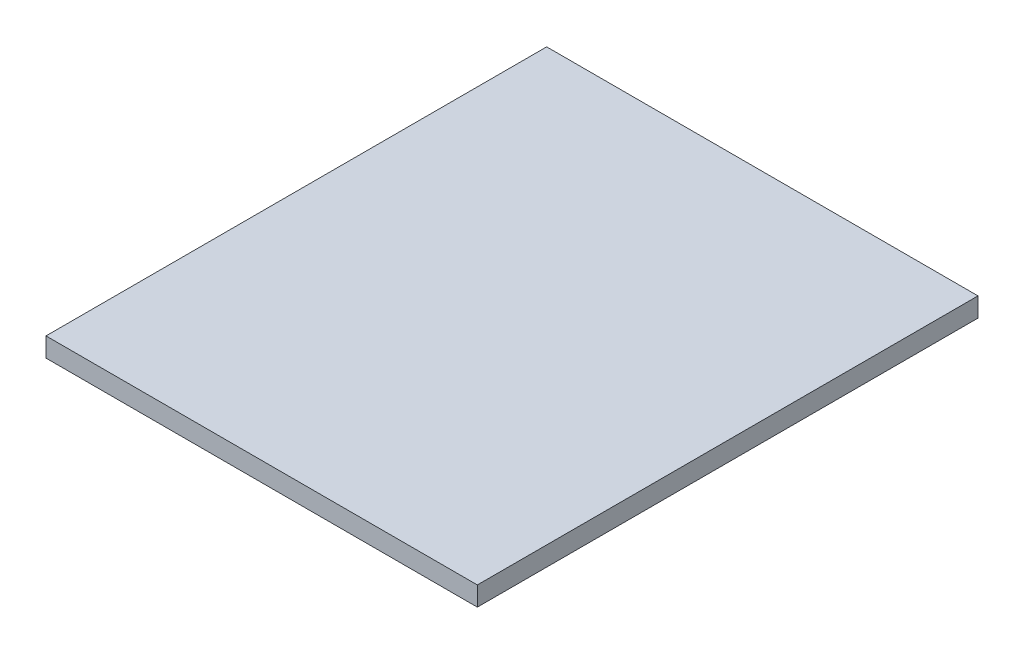
SolidWorks part; units mm, degrees
ref_plane "Front Plane" through (0, 0, 0) normal (0, 0, 1) x (1, 0, 0)
ref_plane "Top Plane" through (0, 0, 0) normal (0, 1, 0) x (1, 0, 0)
ref_plane "Right Plane" through (0, 0, 0) normal (1, 0, 0) x (0, 0, -1)
sketch "Sketch1" plane through (0, 0, 0) normal (0, 1, 0) x (1, 0, 0)
  line L0 (-6, 130) -> (106, 130)
  line L1 (-6, 0) -> (106, 0)
  line L6 (-6, 130) -> (-6, 0)
  line L13 (106, 130) -> (106, 0)
extrude "Boss-Extrude1" add sketch "Sketch1" along normal blind 5
ref_plane "center-of-slot" through (0, 2.5, 0) normal (0, 1, 0) x (1, 0, 0)
ref_plane "center-of-module" through (50, 0, 0) normal (1, 0, 0) x (0, 0, -1)
